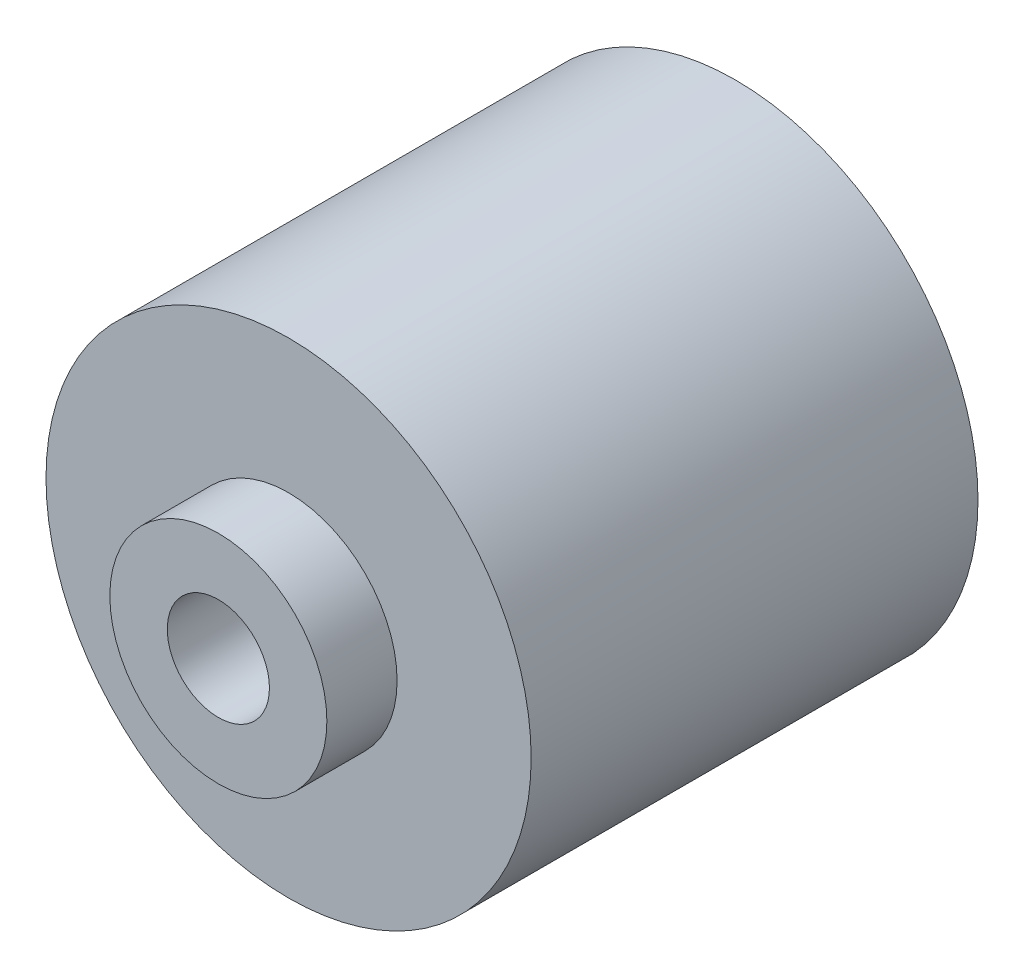
SolidWorks part; units mm, degrees
ref_plane "Front Plane" through (0, 0, 0) normal (0, 0, 1) x (1, 0, 0)
ref_plane "Top Plane" through (0, 0, 0) normal (0, 1, 0) x (1, 0, 0)
ref_plane "Right Plane" through (0, 0, 0) normal (1, 0, 0) x (0, 0, -1)
sketch "Sketch1" plane through (0, 0, 0) normal (0, 0, 1) x (1, 0, 0)
  circle A0 centre (0, 0) radius 19
  dimension "D1" = 38
extrude "Boss-Extrude1" add sketch "Sketch1" along normal blind 35 contours A0
sketch "Sketch5" plane through (0, 0, 35) normal (0, 0, 1) x (1, 0, 0)
  circle A0 centre (0, 0) radius 8.5
  dimension "D1" = 17
extrude "Boss-Extrude3" add sketch "Sketch5" along normal blind 5.5 contours A0
sketch "Sketch6" plane through (0, 0, 40.5) normal (0, 0, 1) x (1, 0, 0)
  circle A0 centre (0, 0) radius 4
  dimension "D1" = 8
extrude "Cut-Extrude3" cut sketch "Sketch6" against normal blind 10
